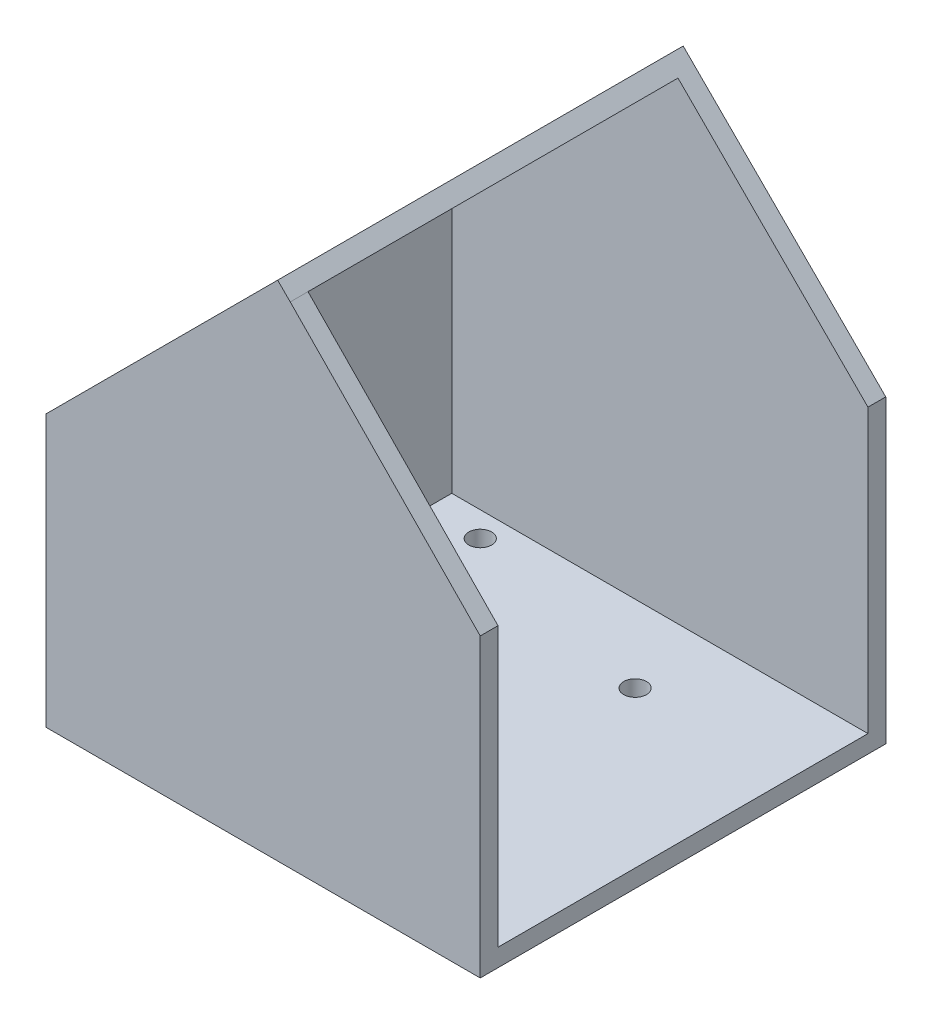
SolidWorks part; units mm, degrees
ref_plane "前视基准面" through (0, 0, 0) normal (0, 0, 1) x (1, 0, 0)
ref_plane "上视基准面" through (0, 0, 0) normal (0, 1, 0) x (1, 0, 0)
ref_plane "右视基准面" through (0, 0, 0) normal (1, 0, 0) x (0, 0, -1)
sketch "草图1" plane through (0, 0, 0) normal (0, 0, 1) x (1, 0, 0)
  line L0 (32.5269, 70.7116) -> (0, 38.1847)
  line L1 (0, 38.1847) -> (0, 0)
  line L2 (0, 0) -> (100.7385, 0)
  line L4 (0, 38.1847) -> (28.2843, 9.9004) construction
  line L6 (32.4948, 67.144) -> (2.5, 37.1492)
  line L7 (2.5, 37.1492) -> (2.5, 2.5)
  line L8 (2.5, 2.5) -> (94.8533, 2.5)
  line L9 (94.8533, 2.5) -> (32.4948, 67.144) construction
  line L10 (100.7385, 0) -> (32.5269, 70.7116) construction
  line L11 (32.5269, 70.7116) -> (34.2947, 68.9438)
  line L12 (34.2947, 68.9438) -> (32.4948, 67.144)
  line L13 (100.7385, 0) -> (100.7385, 2.5)
  line L14 (100.7385, 2.5) -> (94.8533, 2.5)
  line L15 (34.2947, 68.9438) -> (100.7385, 2.5) construction
  dimension "D1" = 45
  dimension "D2" = 46
  dimension "D3" = 40
  dimension "D4" = 45
  dimension "D6" = 2.5
extrude "凸台-拉伸1" add sketch "草图1" along normal blind 52
sketch "草图2" plane through (0, 0, 52) normal (0, 0, 1) x (1, 0, 0)
  line L0 (32.5269, 70.7116) -> (0, 38.1847)
  line L1 (0, 38.1847) -> (0, 0) construction
  line L2 (32.5269, 70.7116) -> (0, 38.1847) construction
  line L3 (0, 38.1847) -> (0, 0)
  line L4 (0, 0) -> (100.7385, 0)
  line L6 (34.2947, 68.9438) -> (32.5269, 70.7116)
  line L7 (100.7385, 0) -> (100.7385, 1)
  line L8 (100.7385, 0) -> (100.7385, 2.5) construction
  line L9 (100.7385, 1) -> (34.2947, 68.9438)
extrude "凸台-拉伸2" add sketch "草图2" along normal blind 2.5
sketch "草图3" plane through (0, 0, 0) normal (0, 0, -1) x (-1, 0, 0)
  line L0 (-32.5269, 70.7116) -> (0, 38.1847)
  line L1 (0, 38.1847) -> (0, 0)
  line L2 (0, 0) -> (-100.7385, 0)
  line L3 (-100.7385, 0) -> (-100.7385, 2.5)
  line L4 (-100.7385, 2.5) -> (-34.2947, 68.9438)
  line L5 (-34.2947, 68.9438) -> (-32.5269, 70.7116)
extrude "凸台-拉伸3" add sketch "草图3" along normal blind 2.5
sketch "草图4" plane through (-19.0923, 19.0923, 0) normal (-0.7071, 0.7071, 0) x (0, 0, 1)
  line L0 (54.5, 73.0007) -> (-2.5, 73.0007) construction
  line L1 (26, 73.0007) -> (26, 40.9046) construction
  line L2 (-10.2305, 52.0007) -> (58.7716, 52.0007) construction
  circle A0 centre (10.5, 67.5007) radius 1.6
  circle A1 centre (41.5, 67.5007) radius 1.6
  circle A2 centre (10.5, 36.5007) radius 1.6
  circle A3 centre (41.5, 36.5007) radius 1.6
  circle A4 centre (26, 52.0007) radius 12.5
  dimension "D1" = 3.2
  dimension "D2" = 5.5
  dimension "D3" = 31
  dimension "D4" = 31
  dimension "D5" = 25
extrude "切除-拉伸1" cut sketch "草图4" against normal blind 5
sketch "草图6" plane through (0, 0, 0) normal (0, -1, 0) x (1, 0, 0)
  line L0 (0, 54.5) -> (100.7385, 54.5) construction
  line L1 (0, 54.5) -> (0, -2.5) construction
  line L2 (0, 26) -> (62.3253, 26) construction
  circle A0 centre (10, 48.5) radius 1.6
  circle A1 centre (10, 3.5) radius 1.6
  circle A2 centre (39.0926, 41.1772) radius 1.6
  circle A3 centre (39.0926, 10.8228) radius 1.6
  dimension "D1" = 3.2
  dimension "D2" = 6
  dimension "D3" = 10
  dimension "D4" = 3.2
  dimension "D5" = 30
extrude "切除-拉伸2" cut sketch "草图6" against normal blind 5
sketch "草图7" plane through (0, 0, 54.5) normal (0, 0, 1) x (1, 0, 0)
  line L0 (61, 42.2385) -> (61, 0)
  line L1 (34.2947, 68.9438) -> (32.5269, 70.7116) construction
  line L2 (0, 0) -> (100.7385, 0) construction
  line L3 (61, 0) -> (103.4064, 0)
  line L4 (103.4064, 0) -> (103.4064, 12.7385)
  line L5 (103.4064, 12.7385) -> (61, 42.2385)
  line L6 (0, 38.1847) -> (0, 0) construction
  point P12 (103.4064, 12.7385)
  dimension "D1" = 61
extrude "切除-拉伸3" cut sketch "草图7" against normal through all
